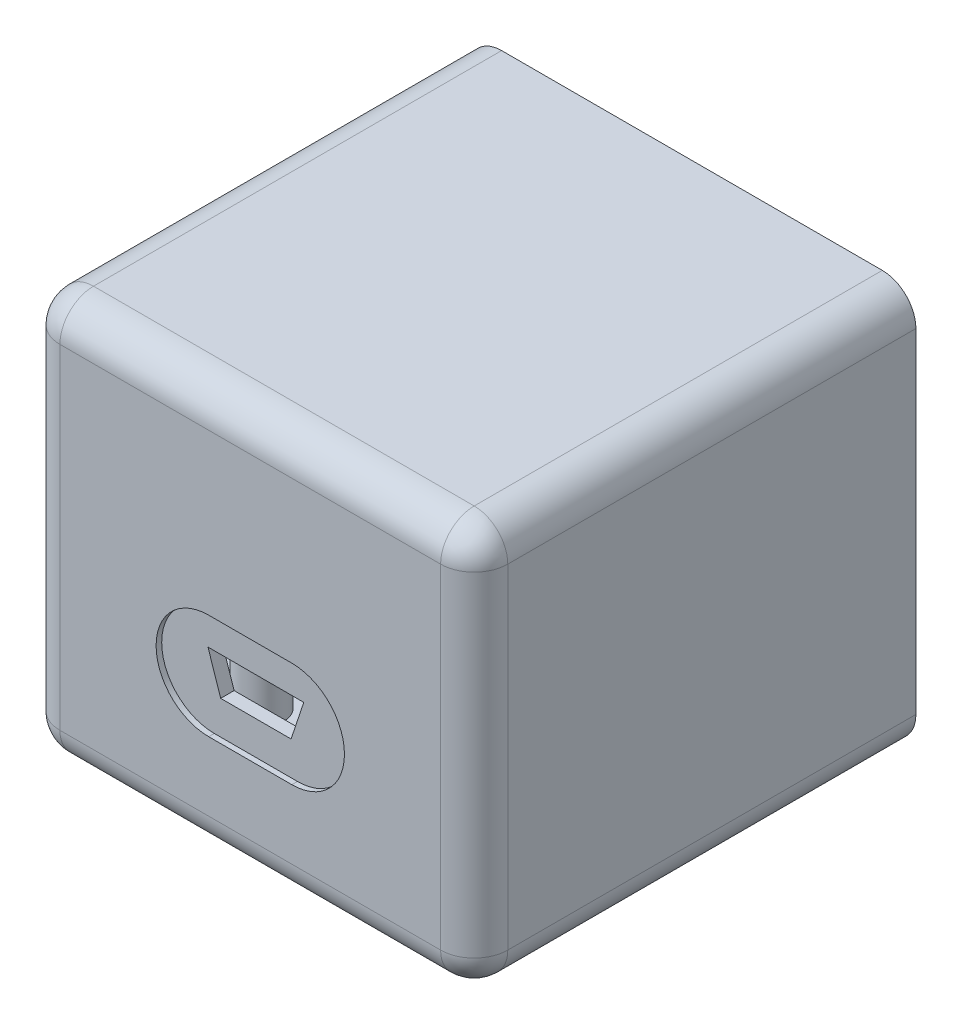
SolidWorks part; units mm, degrees
ref_plane "Plan de face" through (0, 0, 0) normal (0, 0, 1) x (1, 0, 0)
ref_plane "Plan de dessus" through (0, 0, 0) normal (0, 1, 0) x (1, 0, 0)
ref_plane "Plan de droite" through (0, 0, 0) normal (1, 0, 0) x (0, 0, -1)
sketch "Esquisse1" plane through (0, 0, 0) normal (0, 0, 1) x (1, 0, 0)
  line L0 (-20, -17.91) -> (-20, 15.91) construction
  line L2 (20, -17.91) -> (-20, -17.91) construction
  line L3 (20, 15.91) -> (20, -17.91) construction
  line L4 (-20, -17.91) -> (-20, 17.9413)
  line L5 (-20, 17.9413) -> (20, 17.9413)
  line L6 (20, -17.91) -> (-20, -17.91)
  line L7 (20, 17.9413) -> (20, -17.91)
  line L8 (-13.78, 13.91) -> (-6, 13.91) construction
  line L9 (-16.07, 14.21) -> (16.07, 14.21)
  line L10 (-16.07, 14.21) -> (-16.07, -14.21)
  line L11 (-16.07, -14.21) -> (16.07, -14.21)
  line L12 (16.07, 14.21) -> (16.07, -14.21)
  line L14 (15.77, 6.71) -> (15.77, -6.71) construction
  line L15 (-15.77, 6.71) -> (-15.77, -6.71) construction
  line L16 (13.78, -13.91) -> (-13.78, -13.91) construction
  dimension "D1" = 0.3
  dimension "D2" = 0.3
  dimension "D3" = 0.3
  dimension "D4" = 0.3
extrude "Boss.-Extru.1" add sketch "Esquisse1" along normal offset from surface (39.45 mm away) 2
sketch "Esquisse6" plane through (0, -14.21, 0) normal (0, 1, 0) x (1, 0, 0)
  line L0 (0, -39.45) -> (0, -4.2233) construction
  line L1 (16.07, -39.45) -> (-16.07, -39.45) construction
  line L2 (-15.77, -37.45) -> (15.77, -37.45) construction
  circle A0 centre (-9, -15.45) radius 2
  circle A1 centre (9, -15.45) radius 2
  circle A2 centre (-9, -29.45) radius 2
  circle A3 centre (9, -29.45) radius 2
  dimension "D1" = 4
  dimension "D2" = 18
  dimension "D3" = 18
  dimension "D4" = 10
  dimension "D5" = 22
extrude "Boss.-Extru.7" add sketch "Esquisse6" along normal up to surface (7.5 mm away)
sketch "Esquisse3" plane through (0, 0, 39.45) normal (0, 0, 1) x (1, 0, 0)
  line L0 (-20, -17.91) -> (-20, 17.9413) construction
  line L1 (-20, 17.9413) -> (20, 17.9413) construction
  line L2 (20, -17.91) -> (-20, -17.91) construction
  line L3 (20, 17.9413) -> (20, -17.91) construction
  line L4 (-20, -17.91) -> (-20, 17.9413)
  line L5 (-20, 17.9413) -> (20, 17.9413)
  line L6 (20, -17.91) -> (-20, -17.91)
  line L7 (20, 17.9413) -> (20, -17.91)
  line L16 (-3.1442, -5.76) -> (3.1442, -5.76)
  line L17 (3.1442, -5.76) -> (4.2775, -2.36)
  line L18 (4.2775, -2.36) -> (-4.2775, -2.36)
  line L19 (-4.2775, -2.36) -> (-3.1442, -5.76)
  line L20 (-3.1442, -5.76) -> (3.1442, -5.76)
  line L21 (3.1442, -5.76) -> (4.2775, -2.36)
  line L22 (4.2775, -2.36) -> (-4.2775, -2.36)
  line L23 (-4.2775, -2.36) -> (-3.1442, -5.76)
  dimension "D1" = 0.2
extrude "Boss.-Extru.5" add sketch "Esquisse3" against normal offset from surface (1.7 mm away) 0.3
sketch "Esquisse4" plane through (0, 0, 39.45) normal (0, 0, 1) x (1, 0, 0)
  line L0 (-3.7108, -4.06) -> (3.7108, -4.06) construction
  line L1 (-4.2775, -2.36) -> (-3.1442, -5.76) construction
  line L2 (3.1442, -5.76) -> (4.2775, -2.36) construction
  line L3 (-3.7108, -4.06) -> (3.7108, -4.06) construction
  line L4 (-3.7108, 0.64) -> (3.7108, 0.64)
  line L5 (-3.7108, -8.76) -> (3.7108, -8.76)
  line L6 (-3.1442, -5.76) -> (3.1442, -5.76) construction
  arc A0 (-3.7108, 0.64) -> (-3.7108, -8.76) centre (-3.7108, -4.06) ccw
  arc A1 (3.7108, -8.76) -> (3.7108, 0.64) centre (3.7108, -4.06) ccw
  point P6 (0, -4.06)
  dimension "D1" = 3
extrude "Enlèv. mat.-Extru.1" cut sketch "Esquisse4" against normal blind 0.5
ref_plane "Plan1" through (0, 0, 1.2) normal (0, 0, -1) x (-1, 0, 0)
sketch "Esquisse8" plane through (0, 0, 1.2) normal (0, 0, -1) x (-1, 0, 0)
  line L0 (16.07, 14.21) -> (16.07, -14.21) construction
  line L1 (16.07, -14.21) -> (-16.07, -14.21) construction
  line L2 (16.07, -10.3787) -> (16.07, -14.21)
  line L3 (16.07, -14.21) -> (10.2687, -14.21)
  line L4 (10.2687, -14.21) -> (10.2687, -11.7787)
  line L5 (16.07, -10.3787) -> (11.6687, -10.3787)
  line L6 (-16.07, 14.21) -> (16.07, 14.21) construction
  line L7 (-16.07, -14.21) -> (-16.07, 14.21) construction
  line L8 (-16.07, 14.21) -> (-9.8687, 14.21)
  line L9 (-16.07, 9.9787) -> (-16.07, 14.21)
  line L10 (-11.6687, 9.9787) -> (-16.07, 9.9787)
  line L11 (-9.8687, 11.7787) -> (-9.8687, 14.21)
  arc A0 (11.6687, -10.3787) -> (10.2687, -11.7787) centre (11.6687, -11.7787) ccw
  circle A1 centre (-11.6687, 11.7787) radius 1.1
  arc A3 (-11.6687, 9.9787) -> (-9.8687, 11.7787) centre (-11.6687, 11.7787) ccw
  circle A4 centre (11.6687, -11.7787) radius 1.1
  dimension "D1" = 2.4313
  dimension "D3" = 2.8
  dimension "D4" = 2.2
  dimension "D7" = 3.6
  dimension "D8" = 2.2
  dimension "D2" = 4.4013
  dimension "D5" = 4.4013
  dimension "D6" = 2.4313
extrude "Boss.-Extru.8" add sketch "Esquisse8" against normal blind 2
fillet "Congé1" radius 3 8 edges at (0, 17.9413, 39.45) (-20, 0.0157, 39.45) (20, 0.0157, 39.45) (0, -17.91, 39.45) (20, -17.91, 19.725) (20, 17.9413, 19.725) (-20, -17.91, 19.725) (-20, 17.9413, 19.725)
